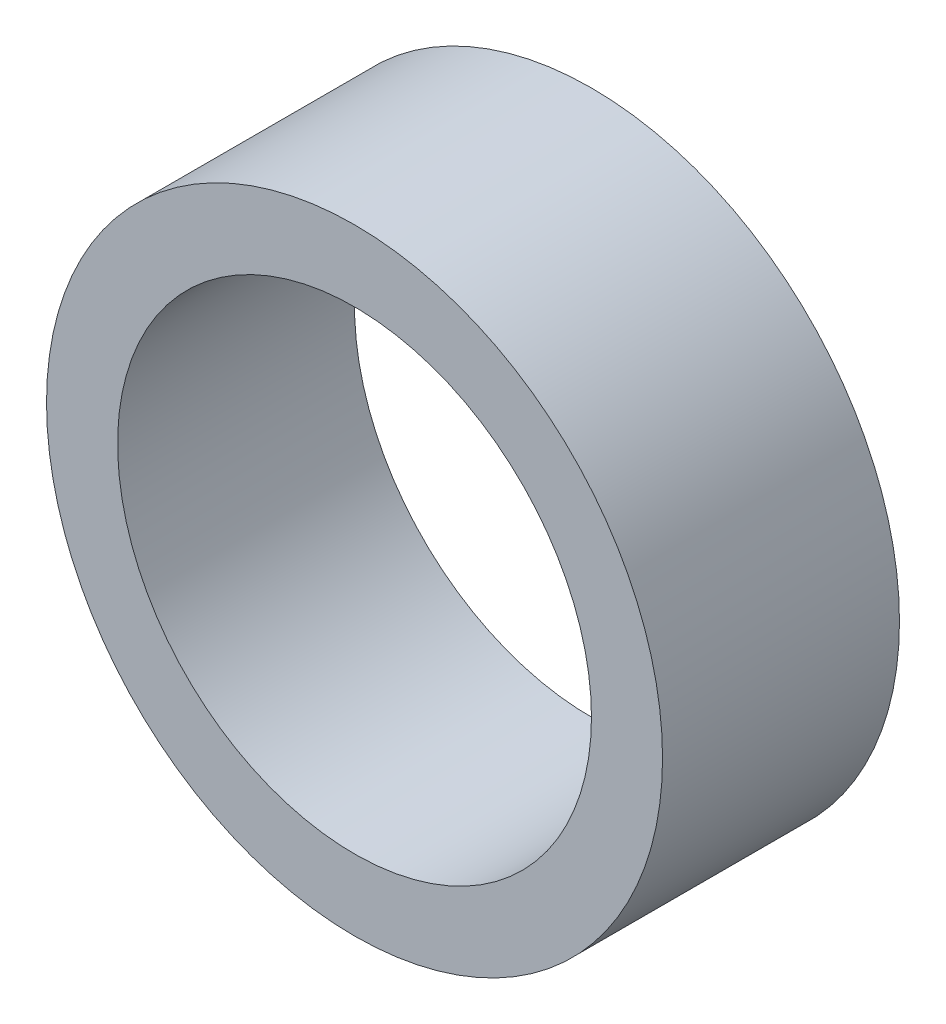
SolidWorks part; units mm, degrees
ref_plane "前视基准面" through (0, 0, 0) normal (0, 0, 1) x (1, 0, 0)
ref_plane "上视基准面" through (0, 0, 0) normal (0, 1, 0) x (1, 0, 0)
ref_plane "右视基准面" through (0, 0, 0) normal (1, 0, 0) x (0, 0, -1)
sketch "草图1" plane through (0, 0, 0) normal (0, 0, 1) x (1, 0, 0)
  circle A0 centre (0, 0) radius 5
  circle A1 centre (0, 0) radius 6.5
  dimension "D1" = 10
  dimension "D2" = 13
extrude "凸台-拉伸1" add sketch "草图1" along normal blind 5
